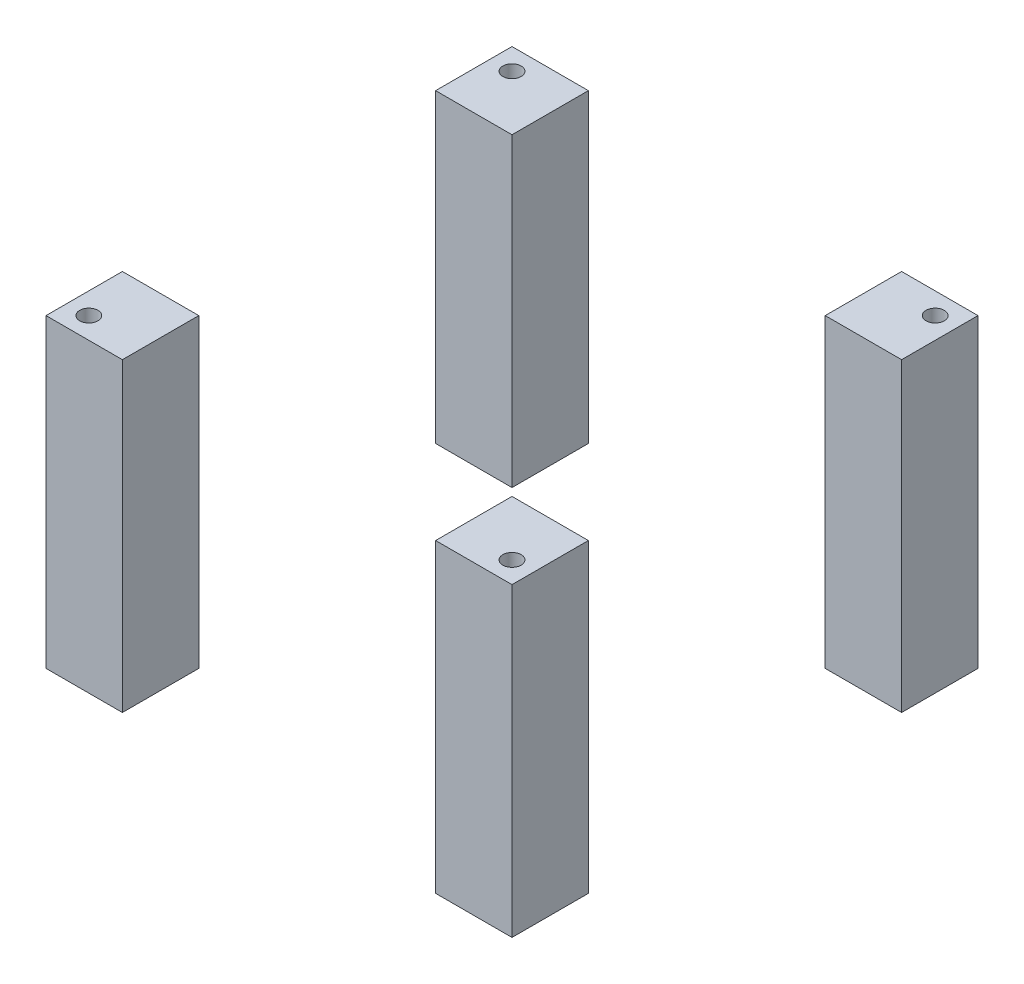
SolidWorks part; units mm, degrees
ref_plane "Front Plane" through (0, 0, 0) normal (0, 0, 1) x (1, 0, 0)
ref_plane "Top Plane" through (0, 0, 0) normal (0, 1, 0) x (1, 0, 0)
ref_plane "Right Plane" through (0, 0, 0) normal (1, 0, 0) x (0, 0, -1)
sketch "Sketch3" plane through (0, 0, 0) normal (0, 1, 0) x (1, 0, 0)
  line L1 (-77.47, -77.47) -> (77.47, -77.47)
  line L2 (-77.47, -77.47) -> (-77.47, 77.47)
  line L3 (-77.47, 77.47) -> (77.47, 77.47)
  line L4 (77.47, -77.47) -> (77.47, 77.47)
  line L5 (-77.47, -77.47) -> (77.47, 77.47) construction
  line L6 (-77.47, 77.47) -> (77.47, -77.47) construction
  point P0 (0, 0)
  dimension "D1" = 154.94
  dimension "D2" = 154.94
extrude "Boss-Extrude3" add sketch "Sketch3" along normal mid plane 12.7
sketch "Sketch4" plane through (0, 6.35, 0) normal (0, 1, 0) x (1, 0, 0)
  line L0 (0, 77.47) -> (0, -77.47) construction
  line L1 (-77.47, 77.47) -> (-52.07, 77.47)
  line L2 (-77.47, 77.47) -> (-77.47, 52.07)
  line L3 (-77.47, 52.07) -> (-52.07, 52.07)
  line L4 (-52.07, 77.47) -> (-52.07, 52.07)
  line L5 (77.47, 77.47) -> (-77.47, 77.47) construction
  line L6 (-77.47, -77.47) -> (77.47, -77.47) construction
  line L7 (77.47, 0) -> (-77.47, 0) construction
  line L8 (77.47, -77.47) -> (77.47, 77.47) construction
  line L9 (-77.47, 77.47) -> (-77.47, -77.47) construction
  line L10 (52.07, 77.47) -> (52.07, 52.07)
  line L11 (77.47, 52.07) -> (52.07, 52.07)
  line L12 (77.47, 77.47) -> (77.47, 52.07)
  line L13 (77.47, 77.47) -> (52.07, 77.47)
  line L14 (77.47, -77.47) -> (52.07, -77.47)
  line L15 (77.47, -77.47) -> (77.47, -52.07)
  line L16 (77.47, -52.07) -> (52.07, -52.07)
  line L17 (52.07, -77.47) -> (52.07, -52.07)
  line L18 (-52.07, -77.47) -> (-52.07, -52.07)
  line L19 (-77.47, -52.07) -> (-52.07, -52.07)
  line L20 (-77.47, -77.47) -> (-77.47, -52.07)
  line L21 (-77.47, -77.47) -> (-52.07, -77.47)
  dimension "D1" = 25.4
extrude "Boss-Extrude4" add sketch "Sketch4" along normal blind 101.6
sketch "Sketch5" plane through (0, 107.95, 0) normal (0, 1, 0) x (1, 0, 0)
  circle A0 centre (70.3501, 70.3501) radius 3.04 construction
  circle A1 centre (-70.3501, 70.3501) radius 3.04 construction
  circle A2 centre (-70.3501, -70.3501) radius 3.04 construction
  circle A3 centre (70.3501, -70.3501) radius 3.04 construction
  circle A4 centre (70.3501, 70.3501) radius 3.04
  circle A5 centre (-70.3501, 70.3501) radius 3.04
  circle A6 centre (-70.3501, -70.3501) radius 3.04
  circle A7 centre (70.3501, -70.3501) radius 3.04
extrude "Cut-Extrude1" cut sketch "Sketch5" against normal blind 19.05
sketch "Sketch6" plane through (0, 0, 0) normal (1, 0, 0) x (0, 0, -1)
  line L2 (-52.07, 6.35) -> (-77.47, 6.35)
  line L3 (-77.47, 6.35) -> (-77.47, -6.35)
  line L4 (52.07, 6.35) -> (77.47, 6.35)
  line L5 (77.47, 107.95) -> (77.47, -6.35) construction
  line L6 (77.47, 6.35) -> (77.47, -6.35)
  line L7 (-77.47, -6.35) -> (77.47, -6.35) construction
  line L8 (-52.07, 6.35) -> (52.07, 6.35) construction
  line L9 (-77.47, -6.35) -> (77.47, -6.35)
  line L10 (-52.07, 6.35) -> (52.07, 6.35)
extrude "Cut-Extrude2" cut sketch "Sketch6" against normal through all both and the other way through all
